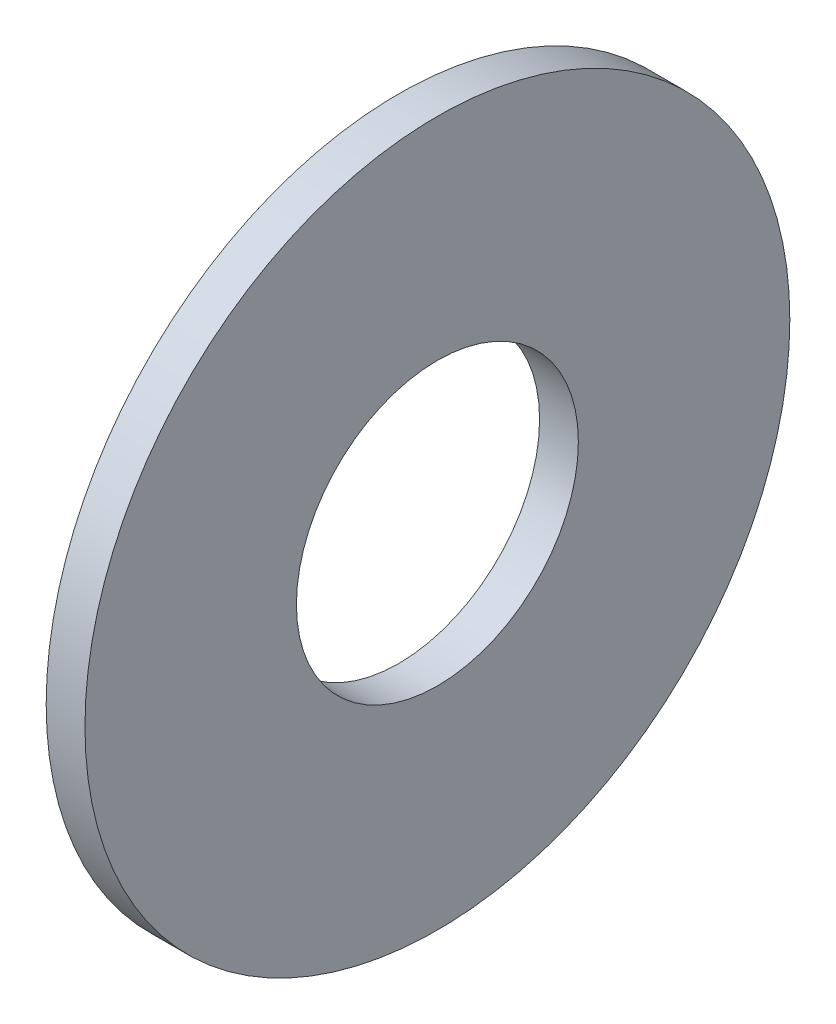
SolidWorks part; units mm, degrees
ref_plane "Plane1" through (0, 0, 0) normal (0, 0, 1) x (1, 0, 0)
ref_plane "Plane2" through (0, 0, 0) normal (0, 1, 0) x (1, 0, 0)
ref_plane "Plane3" through (0, 0, 0) normal (1, 0, 0) x (0, 0, -1)
other "Configuration Table"
sketch "Sketch1" plane through (0, 0, 0) normal (1, 0, 0) x (0, 0, -1)
  circle A0 centre (0, 0) radius 2
  circle A1 centre (0, 0) radius 5
  dimension "Insid_dia" = 4
  dimension "OutsideDia" = 10
extrude "Base-Extrude" add sketch "Sketch1" along normal blind 0.55
